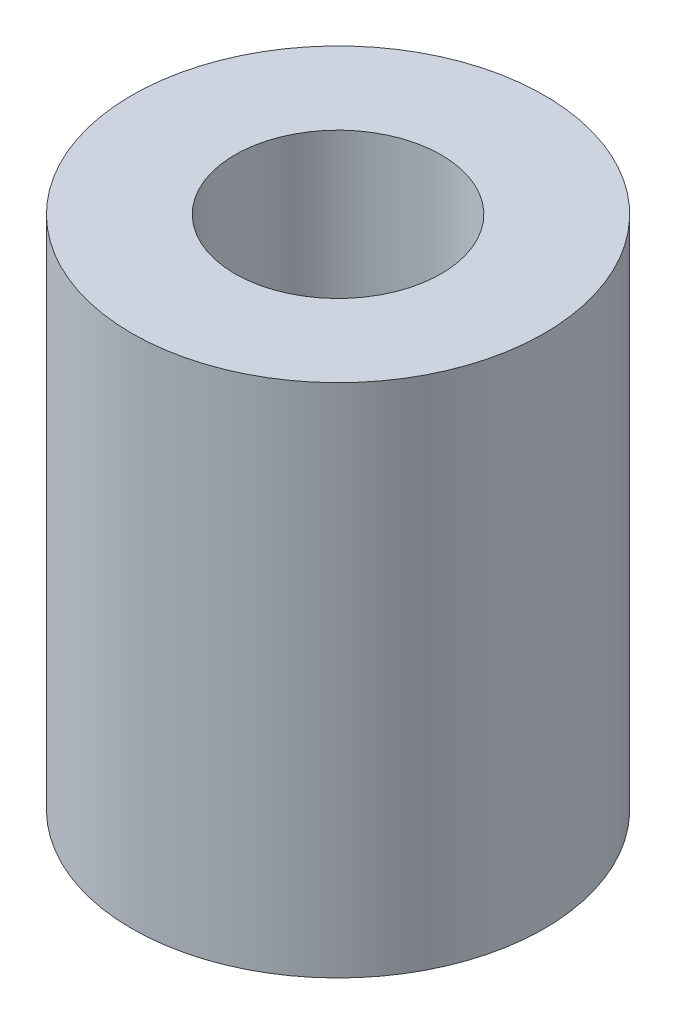
SolidWorks part; units mm, degrees
material "Polyetheretherketone (PEEK)"
ref_plane "Front Plane" through (0, 0, 0) normal (0, 0, 1) x (1, 0, 0)
ref_plane "Top Plane" through (0, 0, 0) normal (0, 1, 0) x (1, 0, 0)
ref_plane "Right Plane" through (0, 0, 0) normal (1, 0, 0) x (0, 0, -1)
sketch "Sketch1" plane through (0, 0, 0) normal (0, 1, 0) x (1, 0, 0)
  circle A0 centre (0, 0) radius 1
  circle A1 centre (0, 0) radius 2
  dimension "D1" = 2
  dimension "D2" = 4
extrude "Boss-Extrude1" add sketch "Sketch1" along normal mid plane 5
